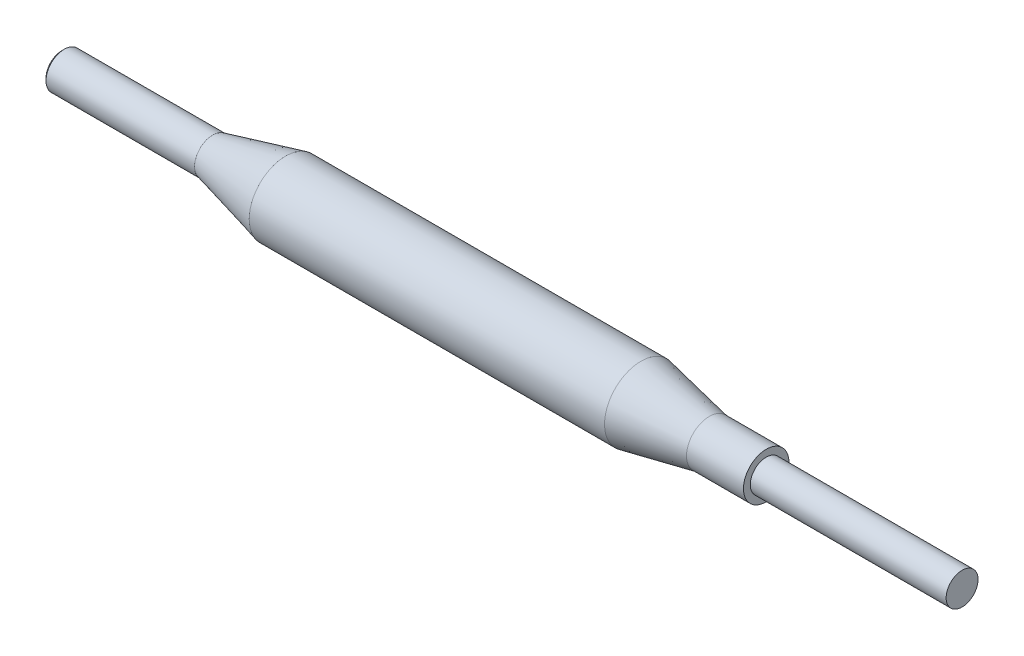
SolidWorks part; units mm, degrees
ref_plane "Ön Düzlem" through (0, 0, 0) normal (0, 0, 1) x (1, 0, 0)
ref_plane "Üst Düzlem" through (0, 0, 0) normal (0, 1, 0) x (1, 0, 0)
ref_plane "Sağ Düzlem" through (0, 0, 0) normal (1, 0, 0) x (0, 0, -1)
sketch "Çizim1" plane through (0, 0, 0) normal (0, 0, 1) x (1, 0, 0)
  line L0 (1.89, 0) -> (250.8821, 0) construction
  line L2 (1.89, 4) -> (35, 4)
  line L3 (35, 4) -> (51, 8)
  line L4 (51, 8) -> (129, 8)
  line L5 (129, 8) -> (144, 5)
  line L6 (144, 5) -> (154.5, 5)
  line L7 (198.5, 3.5) -> (199.49, 3.5)
  line L8 (156.49, 3.5) -> (198.5, 3.5)
  line L10 (1.89, 0) -> (198.5, 0)
  line L11 (154.5, 5) -> (156.49, 5)
  line L12 (156.49, 5) -> (156.49, 3.5)
  line L13 (199.49, 3.5) -> (199.49, 0)
  line L14 (199.49, 0) -> (198.5, 0)
  line L16 (1.89, 4) -> (1.89, 0)
  dimension "D2" = 0.99
  dimension "D3" = 10.5
  dimension "D4" = 15
  dimension "D5" = 3.5
  dimension "D6" = 5
  dimension "D7" = 8
  dimension "D8" = 4
  dimension "D9" = 33.11
  dimension "D10" = 16
  dimension "D11" = 1.99
revolve "Döndür1" add sketch "Çizim1" angle 360 about L0
chamfer "Pah1" distance 0.5 angle 45 1 edges at (1.89, 0, 4)
